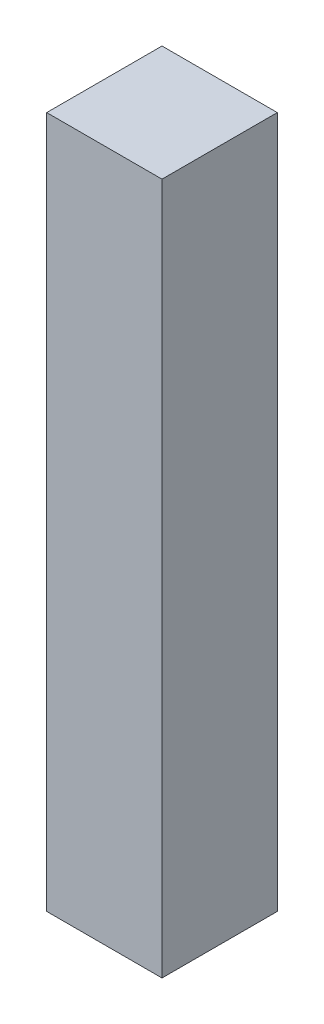
SolidWorks part; units mm, degrees
ref_plane "Front Plane" through (0, 0, 0) normal (0, 0, 1) x (1, 0, 0)
ref_plane "Top Plane" through (0, 0, 0) normal (0, 1, 0) x (1, 0, 0)
ref_plane "Right Plane" through (0, 0, 0) normal (1, 0, 0) x (0, 0, -1)
sketch "Sketch1" plane through (0, 0, 0) normal (0, 1, 0) x (1, 0, 0)
  line L1 (-50.8, -50.8) -> (50.8, -50.8)
  line L2 (-50.8, -50.8) -> (-50.8, 50.8)
  line L3 (-50.8, 50.8) -> (50.8, 50.8)
  line L4 (50.8, -50.8) -> (50.8, 50.8)
  line L5 (-50.8, -50.8) -> (50.8, 50.8) construction
  line L6 (-50.8, 50.8) -> (50.8, -50.8) construction
  point P0 (0, 0)
  dimension "D1" = 101.6
  dimension "D2" = 101.6
extrude "Boss-Extrude1" add sketch "Sketch1" along normal blind 609.6
